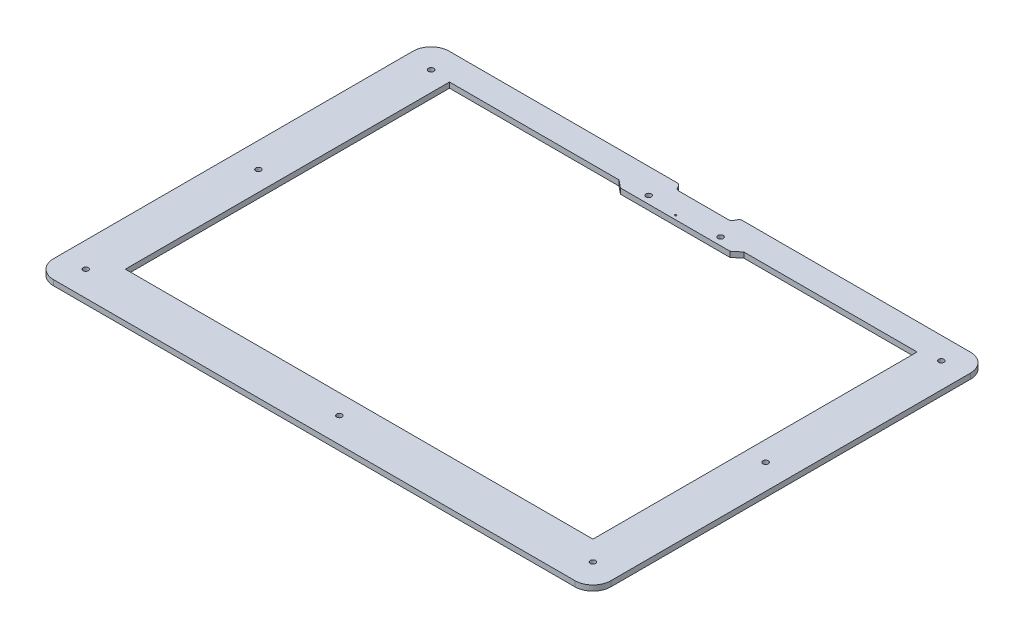
SolidWorks part; units mm, degrees
ref_plane "前视基准面" through (0, 0, 0) normal (0, 0, 1) x (1, 0, 0)
ref_plane "上视基准面" through (0, 0, 0) normal (0, 1, 0) x (1, 0, 0)
ref_plane "右视基准面" through (0, 0, 0) normal (1, 0, 0) x (0, 0, -1)
sketch "草图1" plane through (0, 0, 0) normal (0, 1, 0) x (1, 0, 0)
  line L0 (184.4552, -18.25) -> (188.75, -14.75)
  line L1 (10, 0) -> (136.8844, 0)
  line L2 (0, -10) -> (0, -210)
  line L3 (10, -220) -> (300, -220)
  line L4 (310, -10) -> (310, -210)
  line L5 (28.75, -14.75) -> (47.25, -14.75) construction
  line L6 (28.75, -14.75) -> (28.75, -33.25) construction
  line L7 (28.75, -33.25) -> (47.25, -33.25) construction
  line L8 (173, -85) -> (173, 0) construction
  line L9 (173, -85) -> (310, -85) construction
  line L10 (190, -66) -> (190, 0) construction
  line L11 (215, -58) -> (215, 0) construction
  line L12 (241, -58) -> (241, 0) construction
  line L13 (247, -84) -> (247, 0) construction
  line L14 (222, -84) -> (222, 0) construction
  line L15 (0, -220) -> (310, 0) construction
  line L16 (241, -58) -> (310, -58) construction
  line L17 (247, -84) -> (310, -84) construction
  line L18 (215, -58) -> (310, -58) construction
  line L19 (222, -84) -> (310, -84) construction
  line L20 (190, -66) -> (310, -66) construction
  line L21 (310, -220) -> (0, 0) construction
  line L23 (139.4291, -2.4682) -> (138.6344, -1.0318)
  line L24 (170.5709, -2.4682) -> (171.3656, -1.0318)
  line L25 (173.1156, 0) -> (300, 0)
  line L26 (155, -110) -> (155, -220) construction
  line L27 (47.25, -14.75) -> (47.25, -33.25) construction
  line L28 (28.75, -14.75) -> (47.25, -33.25) construction
  line L29 (28.75, -33.25) -> (47.25, -14.75) construction
  line L30 (52.75, -14.75) -> (71.25, -14.75) construction
  line L31 (52.75, -14.75) -> (52.75, -33.25) construction
  line L32 (52.75, -33.25) -> (71.25, -33.25) construction
  line L33 (71.25, -14.75) -> (71.25, -33.25) construction
  line L34 (52.75, -14.75) -> (71.25, -33.25) construction
  line L35 (52.75, -33.25) -> (71.25, -14.75) construction
  line L36 (76.75, -14.75) -> (95.25, -14.75) construction
  line L37 (76.75, -14.75) -> (76.75, -33.25) construction
  line L38 (76.75, -33.25) -> (95.25, -33.25) construction
  line L39 (95.25, -14.75) -> (95.25, -33.25) construction
  line L40 (76.75, -14.75) -> (95.25, -33.25) construction
  line L41 (76.75, -33.25) -> (95.25, -14.75) construction
  line L42 (100.75, -14.75) -> (119.25, -14.75) construction
  line L43 (100.75, -14.75) -> (100.75, -33.25) construction
  line L44 (100.75, -33.25) -> (119.25, -33.25) construction
  line L45 (119.25, -14.75) -> (119.25, -33.25) construction
  line L46 (100.75, -14.75) -> (119.25, -33.25) construction
  line L47 (100.75, -33.25) -> (119.25, -14.75) construction
  line L48 (188.75, -14.75) -> (207.25, -14.75) construction
  line L49 (188.75, -14.75) -> (188.75, -33.25) construction
  line L50 (188.75, -33.25) -> (207.25, -33.25) construction
  line L51 (207.25, -14.75) -> (207.25, -33.25) construction
  line L52 (188.75, -14.75) -> (207.25, -33.25) construction
  line L53 (188.75, -33.25) -> (207.25, -14.75) construction
  line L54 (212.75, -14.75) -> (231.25, -14.75) construction
  line L55 (212.75, -14.75) -> (212.75, -33.25) construction
  line L56 (212.75, -33.25) -> (231.25, -33.25) construction
  line L57 (231.25, -14.75) -> (231.25, -33.25) construction
  line L58 (212.75, -14.75) -> (231.25, -33.25) construction
  line L59 (212.75, -33.25) -> (231.25, -14.75) construction
  line L60 (236.75, -14.75) -> (255.25, -14.75) construction
  line L61 (236.75, -14.75) -> (236.75, -33.25) construction
  line L62 (236.75, -33.25) -> (255.25, -33.25) construction
  line L63 (255.25, -14.75) -> (255.25, -33.25) construction
  line L64 (236.75, -14.75) -> (255.25, -33.25) construction
  line L65 (236.75, -33.25) -> (255.25, -14.75) construction
  line L66 (260.75, -14.75) -> (279.25, -14.75) construction
  line L67 (260.75, -14.75) -> (260.75, -33.25) construction
  line L68 (260.75, -33.25) -> (279.25, -33.25) construction
  line L69 (279.25, -14.75) -> (279.25, -33.25) construction
  line L70 (260.75, -14.75) -> (279.25, -33.25) construction
  line L71 (260.75, -33.25) -> (279.25, -14.75) construction
  line L73 (123.5448, -18.25) -> (141.1791, -18.25)
  line L74 (141.1791, -18.25) -> (141.1791, -3.5) construction
  line L75 (119.25, -14.75) -> (25, -14.75)
  line L76 (25, -14.75) -> (25, -195)
  line L77 (25, -195) -> (285, -195)
  line L79 (285, -195) -> (285, -14.75)
  line L80 (188.75, -14.75) -> (285, -14.75)
  line L81 (184.4552, -18.25) -> (168.8209, -18.25)
  line L82 (168.8209, -3.5) -> (168.8209, -18.25) construction
  line L83 (123.5448, -18.25) -> (119.25, -14.75)
  line L84 (141.1791, -3.5) -> (168.8209, -3.5)
  line L85 (141.1791, -18.25) -> (168.8209, -18.25)
  arc A0 (10, 0) -> (0, -10) centre (10, -10) ccw
  arc A1 (0, -210) -> (10, -220) centre (10, -210) ccw
  arc A2 (300, -220) -> (310, -210) centre (300, -210) ccw
  arc A3 (300, 0) -> (310, -10) centre (300, -10) cw
  circle A8 centre (173, -85) radius 11 construction
  circle A9 centre (190, -66) radius 11 construction
  circle A11 centre (215, -58) radius 11 construction
  circle A12 centre (222, -84) radius 11 construction
  circle A13 centre (247, -84) radius 11 construction
  circle A14 centre (241, -58) radius 11 construction
  circle A15 centre (14, -14) radius 1.5
  circle A16 centre (14, -206) radius 1.5
  circle A17 centre (296, -206) radius 1.5
  circle A18 centre (296, -12.2857) radius 1.5
  arc A19 (173.1156, 0) -> (171.3656, -1.0318) centre (173.1156, -2) ccw
  arc A20 (170.5709, -2.4682) -> (168.8209, -3.5) centre (168.8209, -1.5) cw
  arc A21 (141.1791, -3.5) -> (139.4291, -2.4682) centre (141.1791, -1.5) cw
  arc A22 (136.8844, 0) -> (138.6344, -1.0318) centre (136.8844, -2) cw
  circle A24 centre (198, -90) radius 11 construction
  circle A25 centre (114, -130) radius 13.5 construction
  circle A26 centre (190, -130) radius 13.5 construction
  circle A27 centre (155, -206) radius 1.5
  circle A28 centre (175, -14) radius 1.5
  circle A29 centre (145, -138) radius 11 construction
  circle A30 centre (106, -90) radius 11 construction
  circle A31 centre (84, -77) radius 11 construction
  circle A32 centre (58, -80) radius 11 construction
  circle A33 centre (36, -97) radius 11 construction
  circle A34 centre (89, -53) radius 11 construction
  circle A35 centre (266, -66) radius 11 construction
  circle A36 centre (110, -24) radius 4.5 construction
  circle A37 centre (86, -24) radius 4.5 construction
  circle A38 centre (62, -24) radius 4.5 construction
  circle A39 centre (38, -24) radius 4.5 construction
  circle A40 centre (198, -24) radius 4.5 construction
  circle A41 centre (222, -24) radius 4.5 construction
  circle A42 centre (246, -24) radius 4.5 construction
  circle A43 centre (270, -24) radius 4.5 construction
  circle A48 centre (135, -14) radius 1.5
  circle A51 centre (296, -110) radius 1.5
  circle A52 centre (14, -110) radius 1.5
  circle A53 centre (152, -16) radius 0.5
  point P8 (0, 0)
  point P12 (0, -220)
  point P15 (310, -220)
  point P18 (310, 0)
  point P70 (171.9365, 0)
  point P73 (170, -3.5)
  point P76 (140, -3.5)
  point P79 (138.0635, 0)
  dimension "D3" = 10
  dimension "D7" = 90
  dimension "D10" = 22
  dimension "D15" = 53
  dimension "D16" = 22
  dimension "D19" = 22
  dimension "D20" = 22
  dimension "D21" = 22
  dimension "D22" = 84
  dimension "D23" = 22
  dimension "D24" = 22
  dimension "D32" = 22
  dimension "D34" = 3
  dimension "D37" = 3
  dimension "D40" = 3
  dimension "D43" = 3
  dimension "D47" = 3.5
  dimension "D50" = 140
  dimension "D51" = 2
  dimension "D52" = 90
  dimension "D54" = 27
  dimension "D56" = 27
  dimension "D59" = 3
  dimension "D61" = 14
  dimension "D62" = 3
  dimension "D64" = 22
  dimension "D8" = 22
  dimension "D9" = 22
  dimension "D11" = 22
  dimension "D12" = 22
  dimension "D13" = 22
  dimension "D76" = 9
  dimension "D84" = 9
  dimension "D86" = 3
  dimension "D89" = 18.5
  dimension "D92" = 18.5
  dimension "D95" = 18.5
  dimension "D98" = 3
  dimension "D101" = 18.5
  dimension "D103" = 18.5
  dimension "D87" = 3
  dimension "D109" = 14.75
  dimension "D118" = 4.2948
  dimension "D120" = 4.2948
  dimension "D119" = 1.75
  dimension "D121" = 1
  dimension "D1" = 220
  dimension "D2" = 310
  dimension "D14" = 89
  dimension "D17" = 85
  dimension "D18" = 137
  dimension "D25" = 66
  dimension "D26" = 120
  dimension "D27" = 36
  dimension "D28" = 58
  dimension "D29" = 95
  dimension "D30" = 88
  dimension "D31" = 69
  dimension "D33" = 63
  dimension "D35" = 14
  dimension "D36" = 14
  dimension "D38" = 14
  dimension "D39" = 14
  dimension "D41" = 14
  dimension "D42" = 14
  dimension "D44" = 14
  dimension "D45" = 12.2857
  dimension "D46" = 4
  dimension "D48" = 30
  dimension "D49" = 4
  dimension "D53" = 112
  dimension "D55" = 114
  dimension "D57" = 90
  dimension "D58" = 120
  dimension "D60" = 14
  dimension "D63" = 135
  dimension "D65" = 82
  dimension "D66" = 145
  dimension "D67" = 97
  dimension "D68" = 80
  dimension "D69" = 58
  dimension "D70" = 84
  dimension "D71" = 77
  dimension "D72" = 90
  dimension "D73" = 106
  dimension "D74" = 44
  dimension "D75" = 66
  dimension "D78" = 24
  dimension "D79" = 110
  dimension "D80" = 24
  dimension "D82" = 24
  dimension "D83" = 24
  dimension "D85" = 40
  dimension "D88" = 18.5
  dimension "D90" = 18.5
  dimension "D91" = 18.5
  dimension "D93" = 18.5
  dimension "D94" = 18.5
  dimension "D96" = 18.5
  dimension "D97" = 18.5
  dimension "D99" = 14
  dimension "D100" = 135
  dimension "D102" = 18.5
  dimension "D104" = 18.5
  dimension "D105" = 18.5
  dimension "D106" = 18.5
  dimension "D107" = 25
  dimension "D108" = 25
  dimension "D110" = 14.75
  dimension "D111" = 17.6344
  dimension "D112" = 15.6344
  dimension "D113" = 94.25
  dimension "D114" = 141.1791
  dimension "D115" = 141.1791
  dimension "D116" = 18.25
  dimension "D117" = 18.25
  dimension "D122" = 152
  dimension "D123" = 16
  dimension "D77" = 4
  dimension "D81" = 4
extrude "凸台-拉伸1" add sketch "草图1" along normal blind 3
